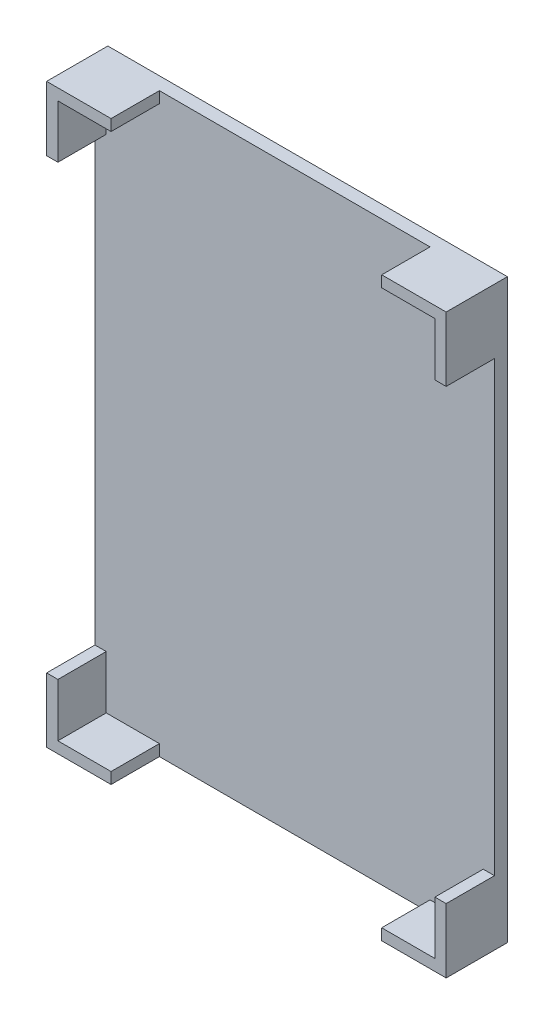
SolidWorks part; units mm, degrees
ref_plane "前基準面" through (0, 0, 0) normal (0, 0, 1) x (1, 0, 0)
ref_plane "上基準面" through (0, 0, 0) normal (0, 1, 0) x (1, 0, 0)
ref_plane "右基準面" through (0, 0, 0) normal (1, 0, 0) x (0, 0, -1)
sketch "草圖1" plane through (0, 0, 0) normal (0, 0, 1) x (1, 0, 0)
  line L1 (-62, 89.5) -> (62, 89.5)
  line L2 (-62, 89.5) -> (-62, -89.5)
  line L3 (-62, -89.5) -> (62, -89.5)
  line L4 (62, 89.5) -> (62, -89.5)
  line L5 (-62, 89.5) -> (62, -89.5) construction
  line L6 (-62, -89.5) -> (62, 89.5) construction
  point P0 (0, 0)
  dimension "D1" = 179
  dimension "D2" = 124
extrude "填料-伸長1" add sketch "草圖1" along normal blind 4
sketch "草圖3" plane through (0, 0, 4) normal (0, 0, 1) x (1, 0, 0)
  line L0 (-62, 89.5) -> (-62, 69.5)
  line L1 (-62, 89.5) -> (-62, -89.5) construction
  line L2 (-62, 69.5) -> (-58.5, 69.5)
  line L3 (-58.5, 69.5) -> (-58.5, 86)
  line L4 (-58.5, 86) -> (-42, 86)
  line L5 (-42, 89.5) -> (-62, 89.5)
  line L6 (62, 89.5) -> (-62, 89.5) construction
  line L7 (-42, 86) -> (-42, 89.5)
  line L8 (0, 89.5) -> (0, 58.1381) construction
  line L9 (-62, 0) -> (-38.9932, 0) construction
  line L10 (42, 86) -> (42, 89.5)
  line L11 (42, 89.5) -> (62, 89.5)
  line L12 (58.5, 86) -> (42, 86)
  line L13 (58.5, 69.5) -> (58.5, 86)
  line L14 (62, 69.5) -> (58.5, 69.5)
  line L15 (62, 89.5) -> (62, 69.5)
  line L16 (0, -89.5) -> (0, -58.1381) construction
  line L17 (62, -89.5) -> (62, -69.5)
  line L18 (62, -69.5) -> (58.5, -69.5)
  line L19 (58.5, -69.5) -> (58.5, -86)
  line L20 (58.5, -86) -> (42, -86)
  line L21 (42, -89.5) -> (62, -89.5)
  line L22 (42, -86) -> (42, -89.5)
  line L23 (-42, -86) -> (-42, -89.5)
  line L24 (-42, -89.5) -> (-62, -89.5)
  line L25 (-58.5, -86) -> (-42, -86)
  line L26 (-58.5, -69.5) -> (-58.5, -86)
  line L27 (-62, -69.5) -> (-58.5, -69.5)
  line L28 (-62, -89.5) -> (-62, -69.5)
  dimension "D1" = 3.5
  dimension "D2" = 3.5
  dimension "D3" = 20
  dimension "D4" = 20
extrude "填料-伸長2" add sketch "草圖3" along normal blind 15
